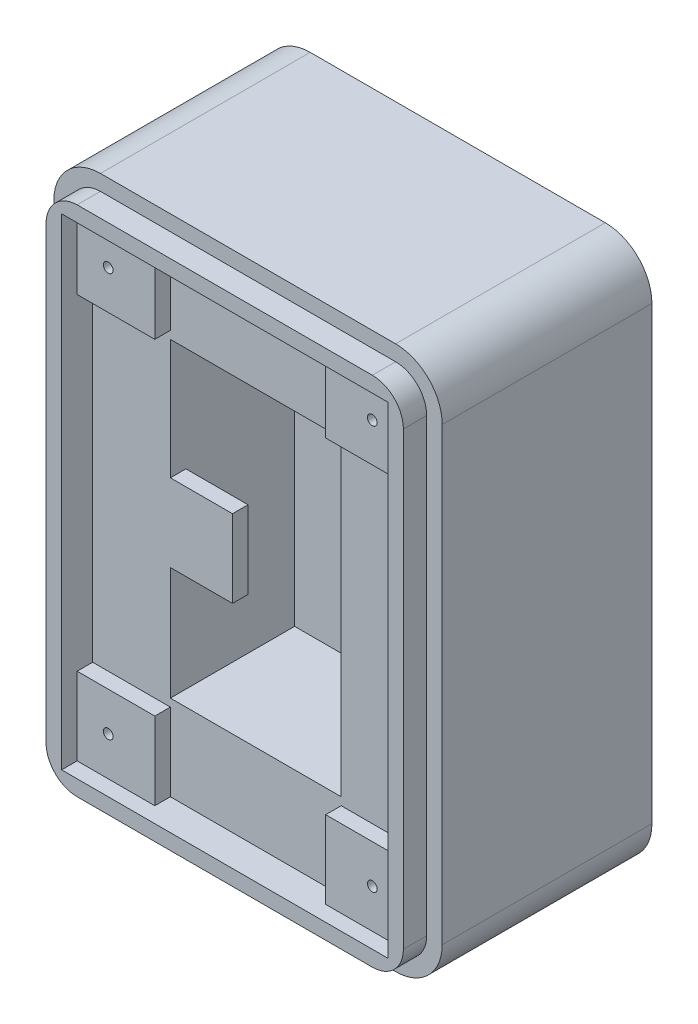
SolidWorks part; units mm, degrees
ref_plane "Front Plane" through (0, 0, 0) normal (0, 0, 1) x (1, 0, 0)
ref_plane "Top Plane" through (0, 0, 0) normal (0, 1, 0) x (1, 0, 0)
ref_plane "Right Plane" through (0, 0, 0) normal (1, 0, 0) x (0, 0, -1)
sketch "Sketch1" plane through (0, 0, 0) normal (0, 0, 1) x (1, 0, 0)
  line L1 (0, 0) -> (63.5, 0)
  line L2 (0, 0) -> (0, -88.9)
  line L3 (0, -88.9) -> (63.5, -88.9)
  line L4 (63.5, 0) -> (63.5, -88.9)
  dimension "D1" = 63.5
  dimension "D2" = 88.9
extrude "Boss-Extrude1" add sketch "Sketch1" along normal blind 38.1
sketch "Sketch2" plane through (0, 0, 38.1) normal (0, 0, 1) x (1, 0, 0)
  line L0 (63.5, 0) -> (0, 0) construction
  line L1 (17.78, -19.05) -> (45.72, -19.05)
  line L2 (17.78, -19.05) -> (17.78, -69.85)
  line L3 (17.78, -69.85) -> (45.72, -69.85)
  line L4 (45.72, -19.05) -> (45.72, -69.85)
  line L5 (63.5, -88.9) -> (63.5, 0) construction
  dimension "D1" = 27.94
  dimension "D2" = 50.8
  dimension "D3" = 19.05
  dimension "D4" = 17.78
extrude "Cut-Extrude1" cut sketch "Sketch2" against normal blind 25.4
sketch "Sketch3" plane through (0, 0, 38.1) normal (0, 0, 1) x (1, 0, 0)
  line L0 (0, 0) -> (0, -88.9) construction
  line L1 (5.08, -5.08) -> (58.42, -5.08)
  line L2 (5.08, -5.08) -> (5.08, -83.82)
  line L3 (5.08, -83.82) -> (58.42, -83.82)
  line L4 (58.42, -5.08) -> (58.42, -83.82)
  line L5 (63.5, 0) -> (0, 0) construction
  dimension "D1" = 53.34
  dimension "D2" = 5.08
  dimension "D3" = 78.74
  dimension "D4" = 5.08
extrude "Cut-Extrude2" cut sketch "Sketch3" against normal blind 5.08
sketch "Sketch4" plane through (17.78, 0, 0) normal (1, 0, 0) x (0, 0, -1)
  line L0 (-33.02, -83.82) -> (-33.02, -5.08) construction
  line L1 (-33.02, -38.658) -> (-30.48, -38.658)
  line L2 (-33.02, -38.658) -> (-33.02, -51.358)
  line L3 (-33.02, -51.358) -> (-30.48, -51.358)
  line L4 (-30.48, -38.658) -> (-30.48, -51.358)
  dimension "D1" = 2.54
  dimension "D2" = 12.7
extrude "Boss-Extrude2" add sketch "Sketch4" along normal blind 10.16
sketch "Sketch5" plane through (0, 0, 33.02) normal (0, 0, 1) x (1, 0, 0)
  line L0 (5.08, -5.08) -> (5.08, -83.82) construction
  line L1 (5.08, -17.78) -> (17.78, -17.78)
  line L2 (5.08, -17.78) -> (5.08, -5.08)
  line L3 (5.08, -5.08) -> (17.78, -5.08)
  line L4 (17.78, -17.78) -> (17.78, -5.08)
  line L5 (58.42, -5.08) -> (5.08, -5.08) construction
  line L6 (58.42, -5.08) -> (5.08, -5.08) construction
  line L7 (45.72, -5.08) -> (58.42, -5.08)
  line L8 (45.72, -5.08) -> (45.72, -17.78)
  line L9 (45.72, -17.78) -> (58.42, -17.78)
  line L10 (58.42, -5.08) -> (58.42, -17.78)
  line L11 (58.42, -83.82) -> (58.42, -5.08) construction
  line L12 (5.08, -5.08) -> (5.08, -83.82) construction
  line L13 (5.08, -71.12) -> (17.78, -71.12)
  line L14 (5.08, -71.12) -> (5.08, -83.82)
  line L15 (5.08, -83.82) -> (17.78, -83.82)
  line L16 (17.78, -71.12) -> (17.78, -83.82)
  line L17 (5.08, -83.82) -> (58.42, -83.82) construction
  line L19 (45.72, -71.12) -> (58.42, -71.12)
  line L20 (45.72, -71.12) -> (45.72, -83.82)
  line L21 (45.72, -83.82) -> (58.42, -83.82)
  line L22 (58.42, -71.12) -> (58.42, -83.82)
  dimension "D1" = 12.7
  dimension "D2" = 12.7
  dimension "D3" = 12.7
  dimension "D4" = 12.7
  dimension "D5" = 12.7
  dimension "D6" = 12.7
  dimension "D7" = 12.7
extrude "Boss-Extrude3" add sketch "Sketch5" along normal blind 2.54
sketch "Sketch7" plane through (0, 0, 35.56) normal (0, 0, 1) x (1, 0, 0)
  line L0 (5.08, -5.08) -> (5.08, -17.78) construction
  line L2 (45.72, -17.78) -> (58.42, -17.78) construction
  line L3 (5.08, -17.78) -> (17.78, -17.78) construction
  line L4 (5.08, -5.08) -> (5.08, -83.82) construction
  line L5 (58.42, -83.82) -> (58.42, -5.08) construction
  circle A0 centre (10.16, -11.43) radius 0.7937
  circle A1 centre (53.34, -11.43) radius 0.7937
  circle A2 centre (10.16, -77.4496) radius 0.7937
  circle A3 centre (53.34, -77.4496) radius 0.7937
  dimension "D3" = 1.5875
  dimension "D4" = 1.5875
  dimension "D7" = 1.5875
  dimension "D8" = 1.5875
  dimension "D1" = 43.18
  dimension "D2" = 5.08
  dimension "D5" = 6.35
  dimension "D6" = 6.35
  dimension "D9" = 5.08
  dimension "D10" = 5.08
  dimension "D11" = 43.18
extrude "Cut-Extrude3" cut sketch "Sketch7" against normal blind 3.81
fillet "Fillet1" radius 7.62 4 edges at (63.5, -88.9, 19.05) (0, -88.9, 19.05) (63.5, 0, 19.05) (0, 0, 19.05)
sketch "Sketch8" plane through (0, 0, 38.1) normal (0, 0, 1) x (1, 0, 0)
  line L0 (2.54, -7.8316) -> (2.54, -81.28)
  line L1 (7.62, -2.54) -> (55.88, -2.54)
  line L2 (60.96, -7.62) -> (60.96, -81.28)
  line L3 (0, -7.62) -> (0, -81.28) construction
  line L4 (55.88, 0) -> (7.62, 0) construction
  line L5 (63.5, -81.28) -> (63.5, -7.62) construction
  line L6 (7.62, -86.36) -> (55.88, -86.36)
  line L7 (7.62, -88.9) -> (55.88, -88.9) construction
  arc A0 (2.54, -81.28) -> (7.62, -86.36) centre (7.62, -81.28) ccw
  arc A1 (55.88, -86.36) -> (60.96, -81.28) centre (55.88, -81.28) ccw
  arc A2 (60.96, -7.62) -> (55.88, -2.54) centre (55.88, -7.62) ccw
  arc A3 (7.62, -2.54) -> (2.54, -7.8316) centre (7.7258, -7.7258) ccw
  line M9 (7.62, -88.9) -> (55.88, -88.9)
  arc M10 (55.88, -88.9) -> (63.5, -81.28) centre (55.88, -81.28) ccw
  line M11 (63.5, -81.28) -> (63.5, -7.62)
  arc M12 (63.5, -7.62) -> (55.88, 0) centre (55.88, -7.62) ccw
  line M13 (55.88, 0) -> (7.62, 0)
  arc M14 (7.62, 0) -> (0, -7.62) centre (7.62, -7.62) ccw
  line M15 (0, -7.62) -> (0, -81.28)
  arc M16 (0, -81.28) -> (7.62, -88.9) centre (7.62, -81.28) ccw
  dimension "D1" = 2.54
  dimension "D2" = 2.54
  dimension "D3" = 2.54
  dimension "D4" = 2.54
extrude "Cut-Extrude4" cut sketch "Sketch8" against normal blind 3.81 contours A3 L1 A2 L2 A1 L6 A0 L0 M16 M9 M10 M11 M12 M13 M14 M15
